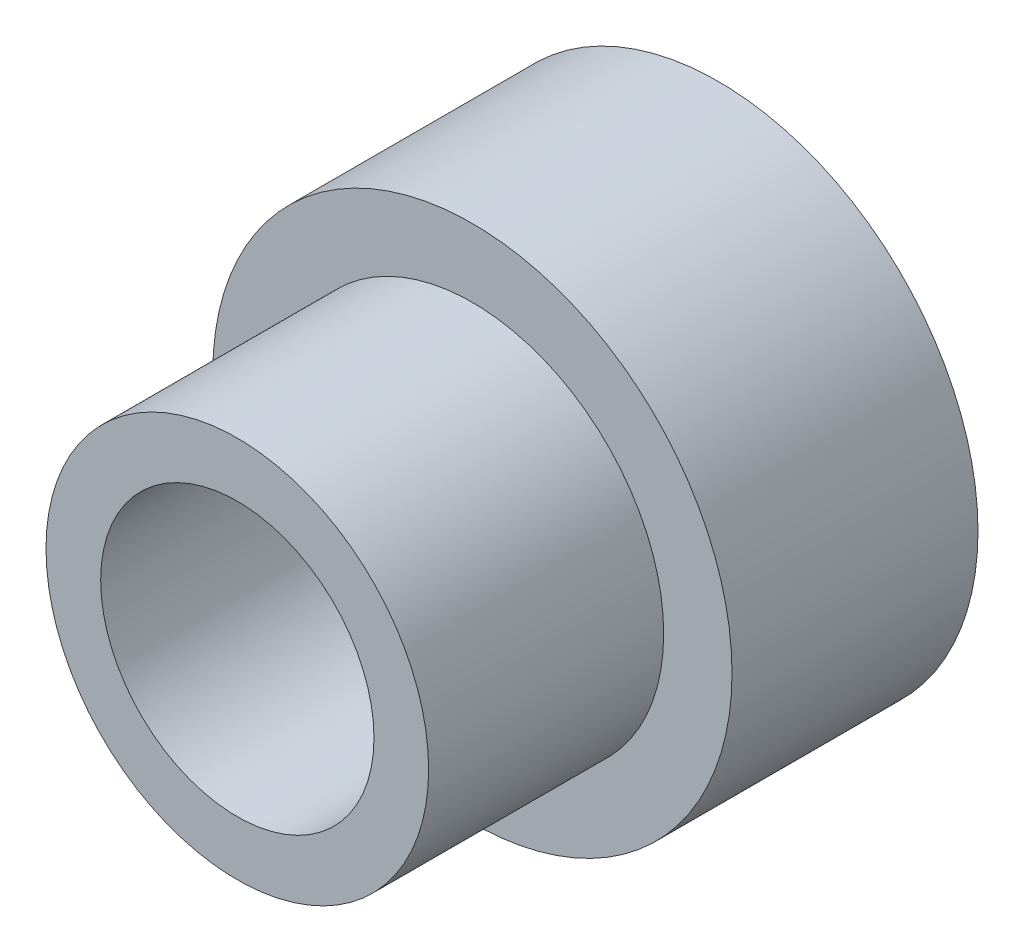
SolidWorks part; units mm, degrees
material "Bronze commercial au plomb"
ref_plane "Plan de face" through (0, 0, 0) normal (0, 0, 1) x (1, 0, 0)
ref_plane "Plan de dessus" through (0, 0, 0) normal (0, 1, 0) x (1, 0, 0)
ref_plane "Plan de droite" through (0, 0, 0) normal (1, 0, 0) x (0, 0, -1)
sketch "Esquisse1" plane through (0, 0, 0) normal (0, 0, 1) x (1, 0, 0)
  circle A0 centre (0, 0) radius 4.75
  dimension "D1" = 9.5
extrude "Boss.-Extru.1" add sketch "Esquisse1" along normal blind 8.8
sketch "Esquisse2" plane through (0, 0, 8.8) normal (0, 0, 1) x (1, 0, 0)
  circle A0 centre (0, 0) radius 3.5
  circle A1 centre (0, 0) radius 4.75
  dimension "D1" = 7
  dimension "D2" = 9.5
extrude "Enlèv. mat.-Extru.1" cut sketch "Esquisse2" against normal blind 4.3
sketch "Esquisse3" plane through (0, 0, 0) normal (0, 0, -1) x (-1, 0, 0)
  circle A0 centre (0, 0) radius 2.5
extrude "Enlèv. mat.-Extru.2" cut sketch "Esquisse3" against normal through all
ref_point "Point1"
ref_plane "Plan1" through (-4.7499, 0.0298, 2.25) normal (-1, 0.0063, 0) x (0, 0, 1)
sketch "Esquisse5" plane through (-4.7499, 0.0298, 2.25) normal (-1, 0.0063, 0) x (0, 0, 1)
  circle A0 centre (0, 0) radius 1.25
  dimension "D1" = 2.5
extrude "Enlèv. mat.-Extru.3" cut sketch "Esquisse5" against normal blind 5
